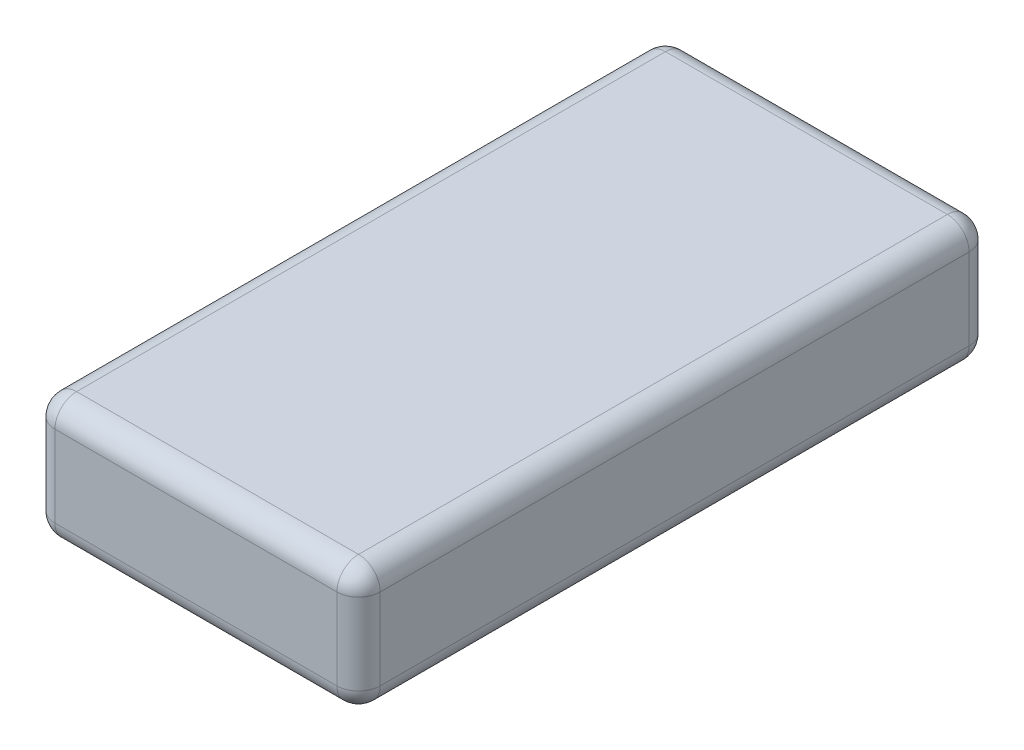
SolidWorks part; units mm, degrees
ref_plane "Front Plane" through (0, 0, 0) normal (0, 0, 1) x (1, 0, 0)
ref_plane "Top Plane" through (0, 0, 0) normal (0, 1, 0) x (1, 0, 0)
ref_plane "Right Plane" through (0, 0, 0) normal (1, 0, 0) x (0, 0, -1)
sketch "Sketch1" plane through (0, 0, 0) normal (0, 1, 0) x (1, 0, 0)
  line L1 (-15, 29.15) -> (15, 29.15)
  line L2 (-15, 29.15) -> (-15, -29.15)
  line L3 (-15, -29.15) -> (15, -29.15)
  line L4 (15, 29.15) -> (15, -29.15)
  line L5 (-15, 29.15) -> (15, -29.15) construction
  line L6 (-15, -29.15) -> (15, 29.15) construction
  point P0 (0, 0)
  dimension "D1" = 30
  dimension "D2" = 58.3
extrude "Boss-Extrude1" add sketch "Sketch1" along normal blind 11.5
fillet "Fillet1" radius 2 12 edges at (15, 5.75, 29.15) (-15, 5.75, 29.15) (15, 5.75, -29.15) (0, 11.5, -29.15) (-15, 5.75, -29.15) (-15, 0, 0) (0, 0, -29.15) (15, 0, 0) (0, 0, 29.15) (0, 11.5, 29.15) (-15, 11.5, 0) (15, 11.5, 0)
